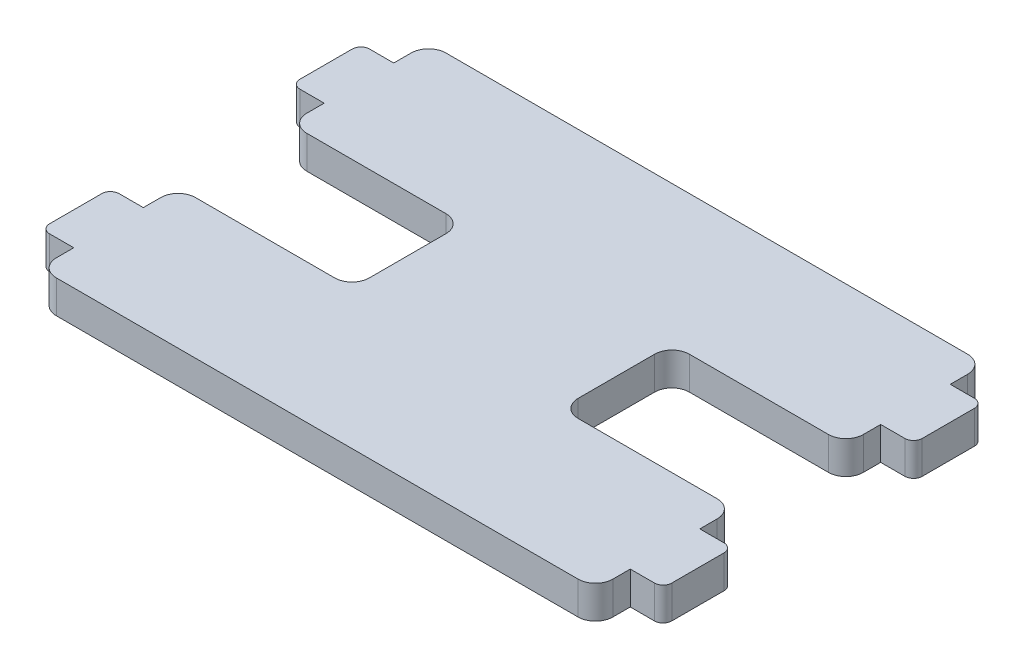
SolidWorks part; units mm, degrees
ref_plane "Front Plane" through (0, 0, 0) normal (0, 0, 1) x (1, 0, 0)
ref_plane "Top Plane" through (0, 0, 0) normal (0, 1, 0) x (1, 0, 0)
ref_plane "Right Plane" through (0, 0, 0) normal (1, 0, 0) x (0, 0, -1)
sketch "Sketch1" plane through (0, 0, 0) normal (0, 1, 0) x (1, 0, 0)
  line L0 (25.4, 5.08) -> (9.525, 5.08)
  line L1 (-25.4, -17.78) -> (-12.458, -17.78)
  line L2 (-25.4, -17.78) -> (-25.4, -5.08)
  line L4 (25.4, -17.78) -> (25.4, -5.08)
  line L5 (-25.4, -17.78) -> (25.4, 17.78) construction
  line L6 (-25.4, 17.78) -> (25.4, -17.78) construction
  line L7 (9.525, 5.08) -> (9.525, -5.08)
  line L8 (9.525, -5.08) -> (25.4, -5.08)
  line L9 (-25.4, -5.08) -> (-9.525, -5.08)
  line L10 (-9.525, -5.08) -> (-9.525, 5.08)
  line L11 (-9.525, 5.08) -> (-25.4, 5.08)
  line L12 (0, -17.78) -> (0, 17.78) construction
  line L13 (-25.4, -5.08) -> (-25.4, 5.08) construction
  line L14 (-25.4, 5.08) -> (-25.4, 17.78)
  line L15 (25.4, -5.08) -> (25.4, 5.08) construction
  line L16 (25.4, 5.08) -> (25.4, 17.78)
  line L20 (0, -17.78) -> (6.592, -17.78)
  line L21 (6.592, -17.78) -> (25.4, -17.78)
  line L22 (-12.458, -17.78) -> (0, -17.78)
  line L27 (-25.4, 17.78) -> (25.4, 17.78)
  point P0 (0, 0)
  point P17 (0, 0)
  point P18 (-9.525, 6.0754)
  dimension "D1" = 50.8
  dimension "D2" = 35.56
  dimension "D3" = 12.7
  dimension "D4" = 12.7
  dimension "D5" = 19.05
extrude "Boss-Extrude1" add sketch "Sketch1" along normal mid plane 3
fillet "Fillet1" radius 1.5875 12 edges at (25.4, 0, -5.08) (9.525, 0, -5.08) (9.525, 0, 5.08) (25.4, 0, 5.08) (25.4, 0, 17.78) (-25.4, 0, 5.08) (-9.525, 0, 5.08) (-9.525, 0, -5.08) (-25.4, 0, -5.08) (-25.4, 0, 17.78) (25.4, 0, -17.78) (-25.4, 0, -17.78)
sketch "Sketch2" plane through (0, 1.5, 0) normal (0, 1, 0) x (1, 0, 0)
  line L0 (-26.9, 11.43) -> (-26.9, -11.43) construction
  line L5 (-25.4, 5.08) -> (-25.4, 17.78) construction
  line L6 (-26.9, 0) -> (0, 0) construction
  line L12 (-25.4, -17.78) -> (-25.4, -5.08) construction
  line L13 (25.4, 5.08) -> (25.4, 17.78) construction
  line L14 (25.4, -17.78) -> (25.4, -5.08) construction
  point P6 (0, 0)
  line B0 (-28.4, 8.255) -> (-25.4, 8.255)
  line B1 (-28.4, 8.255) -> (-28.4, 14.605)
  line B2 (-28.4, 14.605) -> (-25.4, 14.605)
  line B3 (-25.4, 8.255) -> (-25.4, 14.605)
  line B4 (-28.4, 8.255) -> (-25.4, 14.605) construction
  line B5 (-28.4, 14.605) -> (-25.4, 8.255) construction
  line B6 (25.4, 8.255) -> (28.4, 8.255)
  line B7 (25.4, 8.255) -> (25.4, 14.605)
  line B8 (25.4, 14.605) -> (28.4, 14.605)
  line B9 (28.4, 8.255) -> (28.4, 14.605)
  line B10 (25.4, -14.605) -> (28.4, -14.605)
  line B11 (25.4, -14.605) -> (25.4, -8.255)
  line B12 (25.4, -8.255) -> (28.4, -8.255)
  line B13 (28.4, -14.605) -> (28.4, -8.255)
  line B14 (-28.4, -14.605) -> (-25.4, -14.605)
  line B15 (-28.4, -14.605) -> (-28.4, -8.255)
  line B16 (-28.4, -8.255) -> (-25.4, -8.255)
  line B17 (-25.4, -14.605) -> (-25.4, -8.255)
  dimension "D1" = 22.86
sketch_block_instance "Block1-1"
sketch_block "Block1" parameters "D1"=6.35, "D2"=3
sketch_block_instance "Block1-2"
sketch_block_instance "Block1-3"
sketch_block_instance "Block1-4"
extrude "Boss-Extrude2" add sketch "Sketch2" against normal up to surface (3 mm away) up to face at (0, -1.5, 0)
fillet "Fillet2" radius 0.7937 8 edges at (-28.4, 0, 14.605) (-28.4, 0, 8.255) (28.4, 0, 8.255) (28.4, 0, 14.605) (28.4, 0, -14.605) (28.4, 0, -8.255) (-28.4, 0, -14.605) (-28.4, 0, -8.255)
